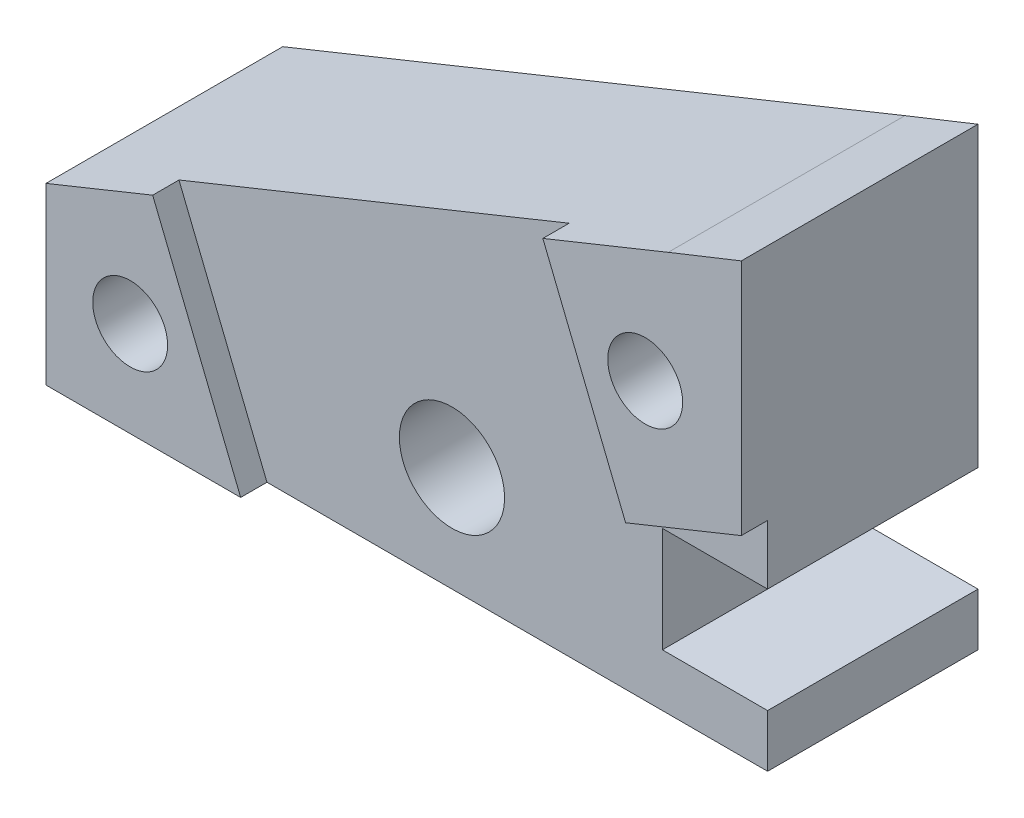
SolidWorks part; units mm, degrees
material "2024 Alloy"
ref_plane "Front Plane" through (0, 0, 0) normal (0, 0, 1) x (1, 0, 0)
ref_plane "Top Plane" through (0, 0, 0) normal (0, 1, 0) x (1, 0, 0)
ref_plane "Right Plane" through (0, 0, 0) normal (1, 0, 0) x (0, 0, -1)
sketch "Sketch1" plane through (0, 0, 0) normal (0, 0, 1) x (1, 0, 0)
  line L0 (6.35, 1.5875) -> (9.525, 1.5875)
  line L1 (9.525, 1.5875) -> (9.525, 4.2246)
  line L2 (6.35, -1.5875) -> (9.525, -1.5875)
  line L3 (9.525, -1.5875) -> (9.525, -3.175)
  line L4 (9.525, -3.175) -> (-11.4587, -3.175)
  line L5 (0, 0) -> (-23.8132, 0) construction
  line L6 (-8.224, 3.404) -> (-3.6768, -7.8507) construction
  line L7 (3.5512, 8.1615) -> (10.5321, -9.1167) construction
  line L9 (-2.3364, 5.7828) -> (1.0962, -2.7131) construction
  line L10 (9.525, 4.2246) -> (9.525, 10.5626)
  line L11 (9.525, 10.5626) -> (7.3193, 9.6839)
  line L13 (0, 0) -> (12.2478, 0) construction
  line L18 (-11.4587, 2.0971) -> (7.3193, 9.6839)
  line L22 (6.35, -1.5875) -> (6.35, 1.5875)
  line L24 (-11.4587, -3.175) -> (-11.4587, 2.0971)
  circle A0 centre (0, 0) radius 1.5875
  circle A1 centre (-8.9187, -0.301) radius 1.1303
  circle A2 centre (6.6246, 5.9789) radius 1.1303
extrude "Boss-Extrude1" add sketch "Sketch1" along normal blind 7.1437
sketch "Sketch3" plane through (0, 0, 7.1437) normal (0, 0, 1) x (1, 0, 0)
  line L0 (-8.3451, 3.6597) -> (-4.8525, -4.985) construction
  line L1 (3.4301, 8.4172) -> (6.3427, 1.2082) construction
  line L2 (-8.3451, 3.6597) -> (-5.4506, -3.5046)
  line L3 (-8.3451, 3.6597) -> (3.4301, 8.4172)
  line L4 (3.4301, 8.4172) -> (6.0341, 1.972)
  line L5 (6.0341, 1.972) -> (9.525, 3.3824)
  line L6 (9.525, 3.3824) -> (9.525, -3.2192)
  line L7 (9.525, -3.2192) -> (-5.4506, -3.5046)
  line L8 (9.525, -3.175) -> (9.525, -1.5875) construction
extrude "Cut-Extrude2" cut sketch "Sketch3" against normal blind 0.7937
